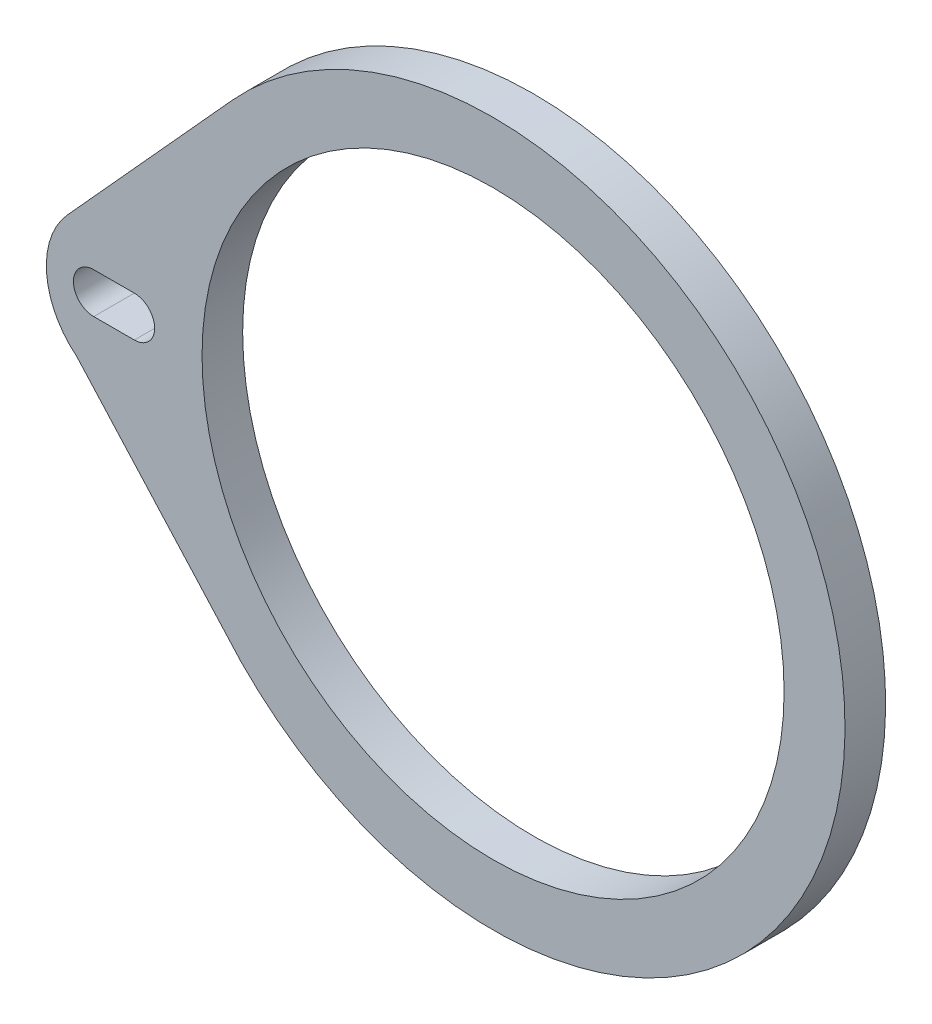
SolidWorks part; units mm, degrees
ref_plane "정면" through (0, 0, 0) normal (0, 0, 1) x (1, 0, 0)
ref_plane "윗면" through (0, 0, 0) normal (0, 1, 0) x (1, 0, 0)
ref_plane "우측면" through (0, 0, 0) normal (1, 0, 0) x (0, 0, -1)
sketch "스케치1" plane through (0, 0, 0) normal (0, 0, 1) x (1, 0, 0)
  line L0 (-22, 0) -> (0, 0) construction
  line L1 (0, 0) -> (22, 0) construction
  line L2 (-22, 0) -> (-27, 0) construction
  line L3 (-19.2593, 17.4666) -> (-31.4444, 4.0307)
  line L5 (-30.7569, -4.6782) -> (-18.6142, -18.1525)
  line L6 (0, 28.8675) -> (0, 0) construction
  line L7 (0, 0) -> (0, -28.8675) construction
  arc A0 (-18.6142, -18.1525) -> (-19.2593, 17.4666) centre (0, 0) ccw
  arc A1 (-31.4444, 4.0307) -> (-30.7569, -4.6782) centre (-27, 0) ccw
  circle A3 centre (0, 0) radius 21 construction
  dimension "D1" = 52
  dimension "D3" = 12
  dimension "D2" = 22
  dimension "D4" = 27
  dimension "D5" = 42
extrude "보스-돌출1" add sketch "스케치1" along normal blind 3
sketch "스케치2" plane through (0, 0, 0) normal (0, 0, -1) x (-1, 0, 0)
  line L0 (0, 0) -> (28, 0) construction
  line L1 (26.5, 0) -> (29.5, 0) construction
  line L2 (26.5, 1.5) -> (29.5, 1.5)
  line L4 (26.5, -1.5) -> (29.5, -1.5)
  circle A0 centre (0, 0) radius 21.5
  arc A1 (26.5, 1.5) -> (26.5, -1.5) centre (26.5, 0) ccw
  arc A2 (29.5, -1.5) -> (29.5, 1.5) centre (29.5, 0) ccw
  point P6 (28, 0)
  dimension "D1" = 43
  dimension "D2" = 28
  dimension "D3" = 3
  dimension "D4" = 1.5
extrude "컷-돌출1" cut sketch "스케치2" against normal blind 10
